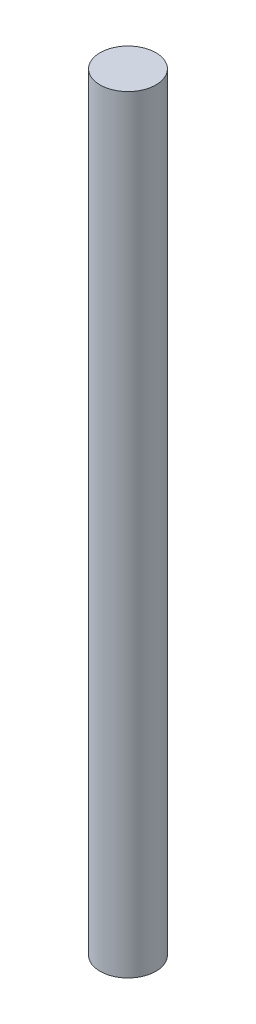
SolidWorks part; units mm, degrees
ref_plane "前视基准面" through (0, 0, 0) normal (0, 0, 1) x (1, 0, 0)
ref_plane "上视基准面" through (0, 0, 0) normal (0, 1, 0) x (1, 0, 0)
ref_plane "右视基准面" through (0, 0, 0) normal (1, 0, 0) x (0, 0, -1)
sketch "Sketch1" plane through (0, 0, 0) normal (0, 1, 0) x (1, 0, 0)
  circle A0 centre (0, 0) radius 4
  dimension "D1" = 8
extrude "Boss-Extrude1" add sketch "Sketch1" along normal blind 110
